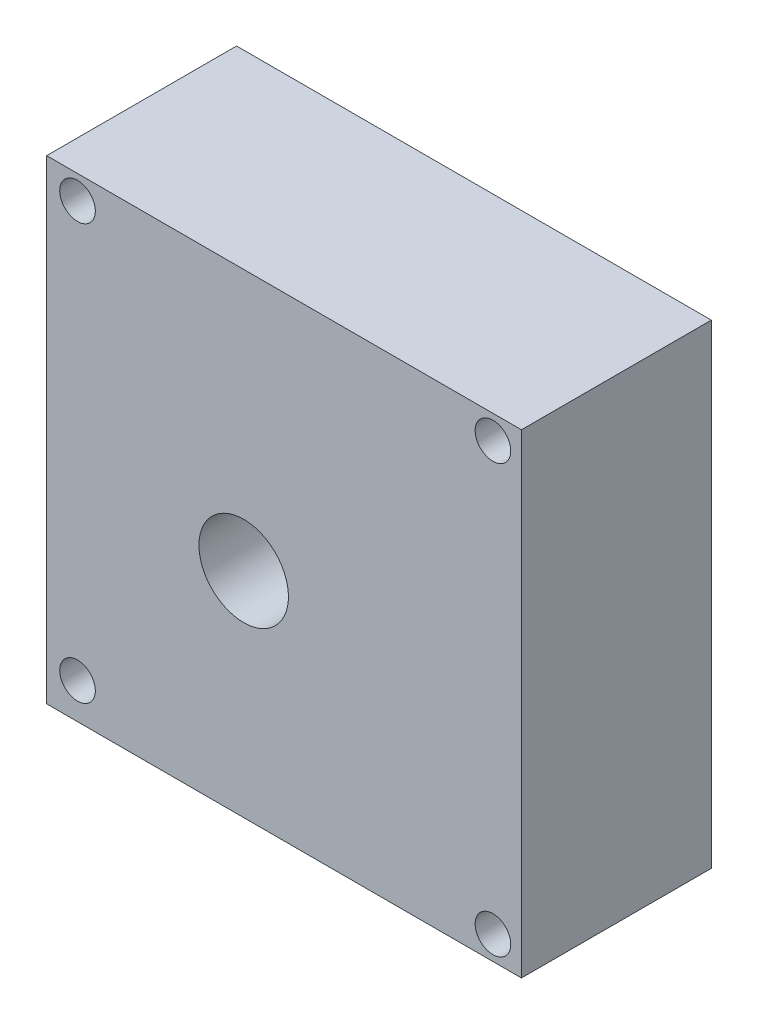
SolidWorks part; units mm, degrees
ref_plane "Front Plane" through (0, 0, 0) normal (0, 0, 1) x (1, 0, 0)
ref_plane "Top Plane" through (0, 0, 0) normal (0, 1, 0) x (1, 0, 0)
ref_plane "Right Plane" through (0, 0, 0) normal (1, 0, 0) x (0, 0, -1)
sketch "Sketch7" plane through (0, 0, 0) normal (0, 0, 1) x (1, 0, 0)
  line L1 (0, 0) -> (50.8, 0)
  line L2 (0, 0) -> (0, 50.8)
  line L3 (0, 50.8) -> (50.8, 50.8)
  line L4 (50.8, 0) -> (50.8, 50.8)
  dimension "D1" = 50.8
  dimension "D2" = 50.8
extrude "Boss-Extrude3" add sketch "Sketch7" along normal blind 20.32
shell "Shell4" thickness 7.62
sketch "Sketch10" plane through (0, 0, 12.7) normal (0, 0, -1) x (-1, 0, 0)
  line L0 (-25.4, 50.8) -> (-25.4, -1.9186) construction
  line L1 (-50.8, 50.8) -> (0, 50.8) construction
  line L2 (-50.8, 25.4) -> (4.8873, 25.4) construction
  line L3 (-50.8, 0) -> (-50.8, 50.8) construction
  line L4 (-47.752, 48.26) -> (5.168, 48.26) construction
  line L5 (-47.752, 48.26) -> (-47.752, -11.78) construction
  line L6 (-3.302, 48.26) -> (-3.302, -5.3516) construction
  line L7 (0, 0) -> (-50.8, 0) construction
  line L8 (0, 50.8) -> (0, 0) construction
  circle A1 centre (-47.752, 48.26) radius 1.905
  circle A6 centre (-3.302, 48.26) radius 1.905
  circle A7 centre (-47.752, 2.54) radius 1.905
  circle A8 centre (-3.302, 3.81) radius 1.905
  point P23 (-48.5251, 2.2722)
  point P24 (0, 0)
  point P27 (0, 2.3111)
  dimension "D1" = 3.81
  dimension "D2" = 45.72
  dimension "D3" = 2.54
  dimension "D4" = 3.048
  dimension "D5" = 3.302
  dimension "D6" = 44.45
  dimension "D7" = 2.54
  dimension "D8" = 44.45
  dimension "D9" = 3.81
extrude "Cut-Extrude4" cut sketch "Sketch10" against normal through all and the other way blind 20.066
sketch "Sketch11" plane through (0, 0, 12.7) normal (0, 0, -1) x (-1, 0, 0)
  line L0 (-50.8, 50.8) -> (0, 50.8) construction
  line L1 (0, 50.8) -> (0, 0) construction
  line L2 (0, 0) -> (-50.8, 0) construction
  circle A0 centre (-21.082, 22.86) radius 4.7879
  dimension "D1" = 9.5758
  dimension "D2" = 27.94
  dimension "D3" = 21.082
  dimension "D4" = 22.86
extrude "Cut-Extrude5" cut sketch "Sketch11" against normal blind 7.62
